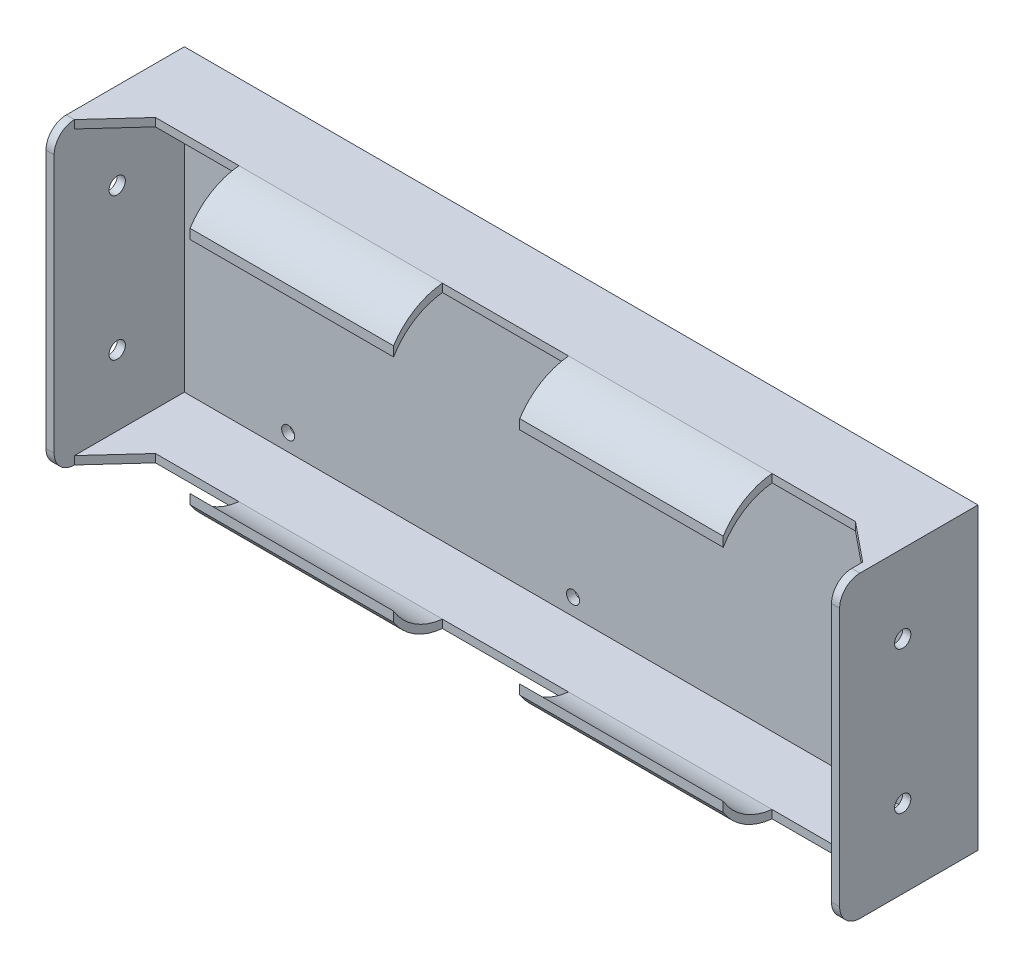
SolidWorks part; units mm, degrees
ref_plane "Front Plane" through (0, 0, 0) normal (0, 0, 1) x (1, 0, 0)
ref_plane "Top Plane" through (0, 0, 0) normal (0, 1, 0) x (1, 0, 0)
ref_plane "Right Plane" through (0, 0, 0) normal (1, 0, 0) x (0, 0, -1)
sketch "Sketch1" plane through (0, 0, 0) normal (0, 0, 1) x (1, 0, 0)
  line L0 (-32.0305, 36.75) -> (248.6114, 36.75) construction
  line L1 (0, 0) -> (195, 0)
  line L2 (0, 0) -> (0, 73.5)
  line L3 (0, 73.5) -> (195, 73.5)
  line L4 (195, 0) -> (195, 73.5)
  line L5 (-22.9162, 67.3641) -> (257.7258, 67.3641) construction
  circle A0 centre (27.5, 67.3641) radius 1.6
  circle A1 centre (97.5, 67.3641) radius 1.6
  circle A2 centre (167.5, 67.3641) radius 1.6
  circle A3 centre (167.5, 6.1359) radius 1.6
  circle A4 centre (97.5, 6.1359) radius 1.6
  circle A5 centre (27.5, 6.1359) radius 1.6
  point P7 (195, 36.75)
  dimension "D3" = 3
  dimension "D1" = 195
  dimension "D2" = 73.5
  dimension "D4" = 97.5
extrude "Boss-Extrude1" add sketch "Sketch1" along normal blind 2
sketch "Sketch2" plane through (0, 0, 2) normal (0, 0, 1) x (1, 0, 0)
  line L0 (0, 0) -> (195, 0) construction
  line L1 (0, 73.5) -> (2, 73.5)
  line L2 (0, 73.5) -> (0, 0)
  line L3 (0, 0) -> (2, 0)
  line L4 (2, 73.5) -> (2, 0)
  line L5 (97.5, 88.4544) -> (97.5, -33.8551) construction
  line L6 (195, 73.5) -> (0, 73.5) construction
  line L7 (195, 73.5) -> (193, 73.5)
  line L8 (195, 73.5) -> (195, 0)
  line L9 (193, 73.5) -> (193, 0)
  line L10 (195, 0) -> (193, 0)
  point P11 (97.5, 73.5)
  dimension "D1" = 2
extrude "Boss-Extrude2" add sketch "Sketch2" along normal blind 32
sketch "Sketch3" plane through (0, 0, 0) normal (0, -1, 0) x (1, 0, 0)
  line L0 (0, 0) -> (0, 29)
  line L1 (0, 34) -> (0, 0) construction
  line L2 (0, 29) -> (2, 29)
  line L3 (2, 34) -> (2, 2) construction
  line L4 (2, 29) -> (11.5, 18.6)
  line L5 (11.5, 18.6) -> (183.5, 18.6)
  line L6 (183.5, 18.6) -> (193, 26.325)
  line L8 (193, 34) -> (193, 2) construction
  line L9 (193, 26.325) -> (195, 26.325)
  line L10 (195, 34) -> (195, 0) construction
  line L11 (195, 26.325) -> (195, 0)
  line L12 (195, 0) -> (0, 0)
  line L13 (0, 34) -> (2, 34) construction
  point P20 (1, 29)
  dimension "D1" = 5
  dimension "D2" = 18.6
  dimension "D3" = 11.5
  dimension "D4" = 11.5
extrude "Boss-Extrude3" add sketch "Sketch3" against normal blind 2
ref_plane "Plane1" through (0, 36.75, 0) normal (0, -1, 0) x (-1, 0, 0)
mirror "Mirror1" about plane through (0, 36.75, 0) normal (0, -1, 0) of "Boss-Extrude3"
ref_plane "Plane2" through (32, 0, 0) normal (-1, 0, 0) x (0, 0, 1)
sketch3d "3DSketch1"
  line L0 (32, 0, 18.6) -> (32, 2, 18.6)
  line L1 (183.5, 0, 18.6) -> (11.5, 0, 18.6) construction
  line L2 (183.5, 2, 18.6) -> (11.5, 2, 18.6) construction
  line L3 (32, 11.9171, 30.6) -> (32, 3.0465, 30.6) construction
  line L4 (32, 9.719, 30.6) -> (32, 7.3344, 30.6)
  arc A0 (32, 0, 18.6) -> (32, 7.3344, 30.6) centre (32, 15.951, 17.0922) cw
  arc A1 (32, 2, 18.6) -> (32, 9.719, 30.6) centre (32, 17.9056, 16.8514) cw
  point P9 (15.9779, 15.951, 17.0922)
  point P12 (15.9986, 17.9056, 16.8514)
  dimension "D1" = 12
extrude "Boss-Extrude4" add sketch "3DSketch1" along direction (-1, 0, 0) on the side of the normal blind 50 contours A0 L4 A1 L0
ref_plane "Plane3" through (97.5, 0, 0) normal (1, 0, 0) x (0, 0, -1)
mirror "Mirror2" about plane through (97.5, 0, 0) normal (1, 0, 0) of "Boss-Extrude4"
mirror "Mirror3" about plane through (0, 36.75, 0) normal (0, -1, 0) of "Mirror2", "Boss-Extrude4"
fillet "Fillet1" radius 5 4 edges at (1, 0, 34) (1, 73.5, 34) (194, 73.5, 34) (194, 0, 34)
sketch "Sketch6" plane through (0, 0, 0) normal (-1, 0, 0) x (0, 0, 1)
  line L0 (5, 41.5103) -> (5, 30.6983) construction
  line L1 (0, 73.5) -> (0, 0) construction
  line L2 (-15.95, 36.75) -> (15.95, 36.75) construction
  circle A0 centre (5, 46.75) radius 1
  circle A1 centre (5, 26.75) radius 1
  dimension "D1" = 5
  dimension "D2" = 20
  dimension "D3" = 10
extrude "Boss-Extrude5" add sketch "Sketch6" along normal blind 15
sketch "Sketch7" plane through (0, 0, 0) normal (-1, 0, 0) x (0, 0, 1)
  line L0 (18.5, 76.3192) -> (18.5, 2.6125) construction
  line L1 (0, 73.5) -> (0, 0) construction
  line L2 (29, 73.5) -> (0, 73.5) construction
  circle A0 centre (18.5, 54.25) radius 2
  circle A1 centre (18.5, 19.25) radius 2
  circle A2 centre (18.5, 19.25) radius 16.575 construction
  dimension "D3" = 19.25
  dimension "D1" = 18.5
  dimension "D2" = 35
extrude "Cut-Extrude1" cut sketch "Sketch7" against normal through all
